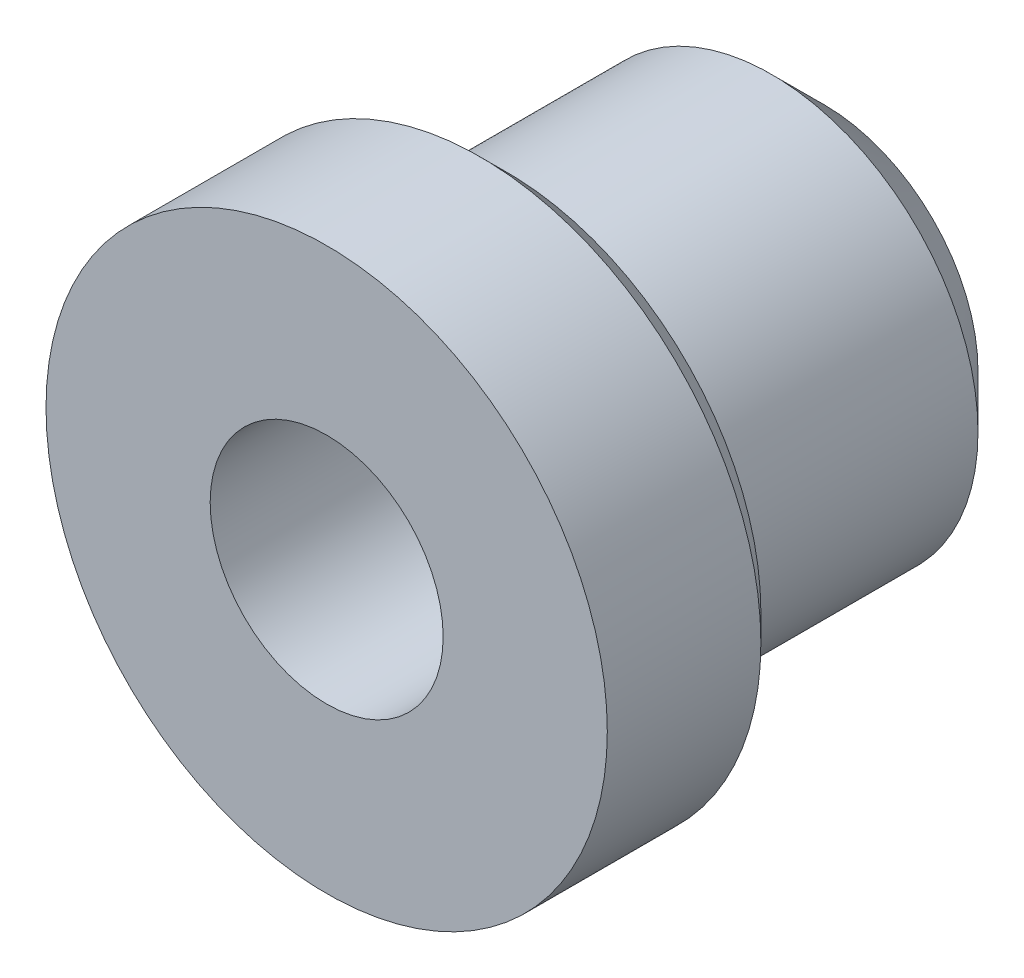
SolidWorks part; units mm, degrees
ref_plane "Front Plane" through (0, 0, 0) normal (0, 0, 1) x (1, 0, 0)
ref_plane "Top Plane" through (0, 0, 0) normal (0, 1, 0) x (1, 0, 0)
ref_plane "Right Plane" through (0, 0, 0) normal (1, 0, 0) x (0, 0, -1)
sketch "Sketch1" plane through (0, 0, 0) normal (0, 0, 1) x (1, 0, 0)
  circle A0 centre (10.0448, -1.2658) radius 1.4
  circle A1 centre (10.0448, -1.2658) radius 3.9
  dimension "D1" = 2.8
  dimension "D2" = 2.5
extrude "Boss-Extrude1" add sketch "Sketch1" along normal up to surface (6 mm away) from offset 1
sketch "Sketch2" plane through (0, 0, 7) normal (0, 0, 1) x (1, 0, 0)
  circle A0 centre (10.0448, -1.2658) radius 5.3
  circle A1 centre (10.0448, -1.2658) radius 1.4
  dimension "D1" = 10.6
extrude "Boss-Extrude2" add sketch "Sketch2" along normal blind 3.4
chamfer "Chamfer1" distance 0.5 angle 45 1 edges at (15.3448, -1.2658, 7)
sketch "Sketch3" plane through (0, 0, 10.4) normal (0, 0, 1) x (1, 0, 0)
  circle A0 centre (10.0448, -1.2658) radius 2.2
  dimension "D1" = 4.4
extrude "Cut-Extrude1" cut sketch "Sketch3" against normal blind 3.2
chamfer "Chamfer2" distance 1 angle 45 1 edges at (13.9448, -1.2658, 1)
